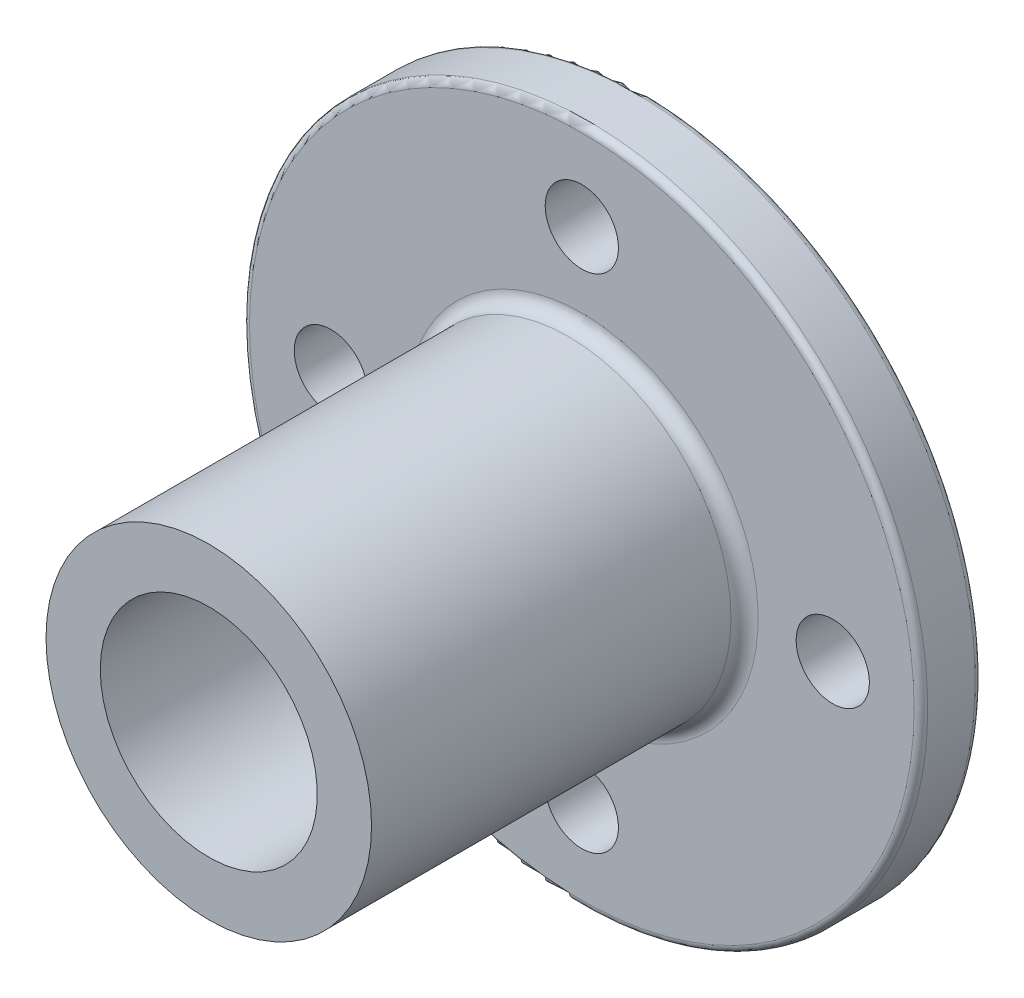
SolidWorks part; units mm, degrees
ref_plane "Front Plane" through (0, 0, 0) normal (0, 0, 1) x (1, 0, 0)
ref_plane "Top Plane" through (0, 0, 0) normal (0, 1, 0) x (1, 0, 0)
ref_plane "Right Plane" through (0, 0, 0) normal (1, 0, 0) x (0, 0, -1)
sketch "Sketch1" plane through (0, 0, 0) normal (1, 0, 0) x (0, 0, -1)
  line L0 (-16, 8) -> (16, 8)
  line L1 (16, 8) -> (16, 24.5)
  line L2 (15.5, 25) -> (12, 25)
  line L3 (11.5, 24.5) -> (11.5, 13)
  line L4 (10.5, 12) -> (-16, 12)
  line L5 (-16, 8) -> (-16, 12)
  line L6 (0, 0) -> (-50000, 0) construction
  arc A0 (11.5, 13) -> (10.5, 12) centre (10.5, 13) cw
  arc A1 (16, 24.5) -> (15.5, 25) centre (15.5, 24.5) ccw
  arc A2 (12, 25) -> (11.5, 24.5) centre (12, 24.5) ccw
  point P2 (0, 8)
  point P12 (16, 25)
  point P15 (11.5, 25)
  dimension "D6" = 1
  dimension "D7" = 0.5
  dimension "D1" = 25
  dimension "D2" = 12
  dimension "D3" = 8
  dimension "D4" = 4.5
  dimension "D5" = 32
revolve "Revolve1" add sketch "Sketch1" angle 360 about L6
sketch "Sketch2" plane through (0, 0, -16) normal (0, 0, -1) x (-1, 0, 0)
  circle A0 centre (0, 18.5) radius 2.7
  circle A1 centre (18.5, 0) radius 2.7
  circle A2 centre (0, -18.5) radius 2.7
  circle A3 centre (-18.5, 0) radius 2.7
  point P12 (0, 0)
  dimension "D1" = 5.4
  dimension "D2" = 18.5
  dimension "D3" = 4
extrude "Cut-Extrude1" cut sketch "Sketch2" against normal through all both and the other way through all
